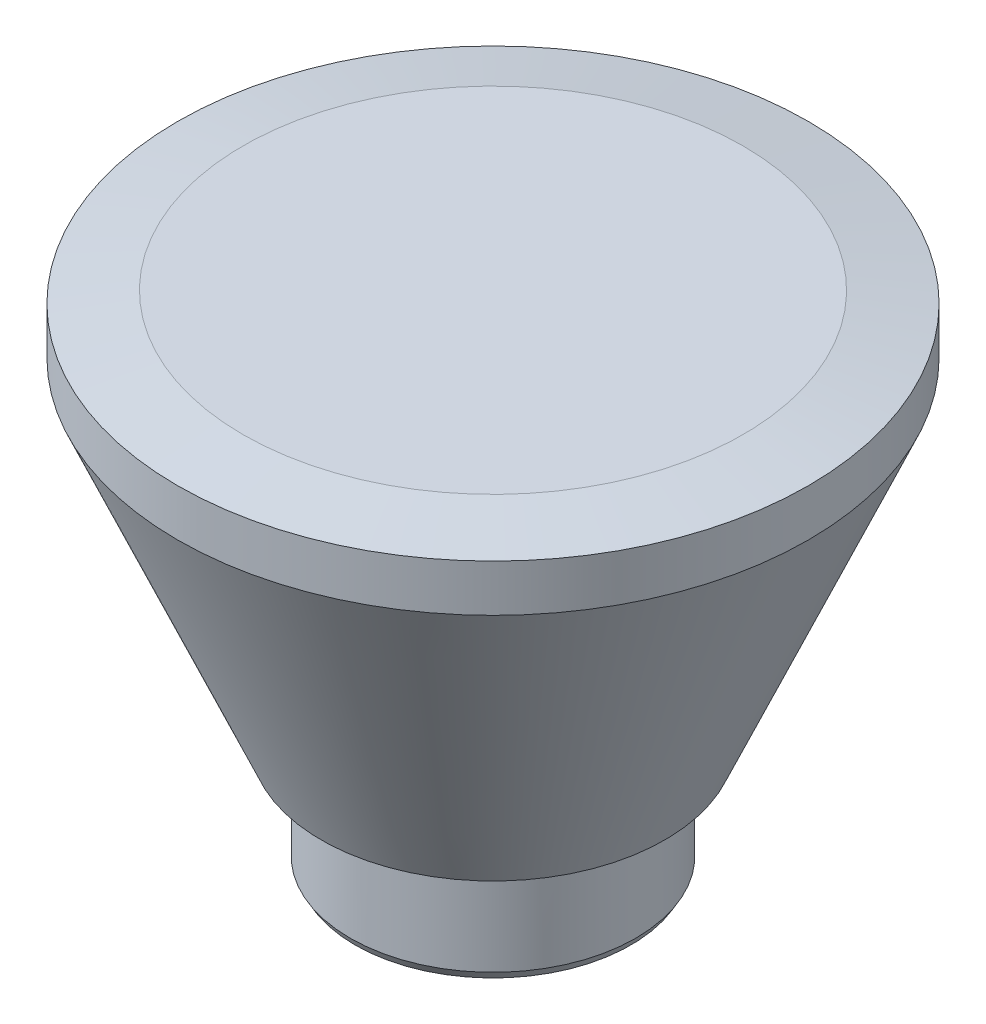
SolidWorks part; units mm, degrees
material "PLA"
ref_plane "Front Plane" through (0, 0, 0) normal (0, 0, 1) x (1, 0, 0)
ref_plane "Top Plane" through (0, 0, 0) normal (0, 1, 0) x (1, 0, 0)
ref_plane "Right Plane" through (0, 0, 0) normal (1, 0, 0) x (0, 0, -1)
sketch "Sketch1" plane through (0, 0, 0) normal (0, 0, 1) x (1, 0, 0)
  line L0 (-19, 22.4817) -> (-15.0608, 23.1763)
  line L2 (0, -1.5737) -> (0, 23.1763)
  line L3 (0, 23.1763) -> (-15.0608, 23.1763)
  line L4 (-19, 19.6513) -> (-19, 22.4817)
  line L6 (-5.6, 3.4263) -> (-3, 3.4263)
  line L12 (-8.6, -0.3237) -> (-8.6, -6.8237)
  line L13 (-8.6, -6.8237) -> (-5.6, -6.8237)
  line L14 (-5.6, -6.8237) -> (-5.6, 3.4263)
  line L15 (-10.35, 0.6763) -> (-10.35, -0.3237) construction
  line L16 (-10.35, -0.3237) -> (-8.6, -0.3237)
  line L20 (-3, 3.4263) -> (-3, -1.5737)
  line L21 (-3, -1.5737) -> (0, -1.5737)
  line L22 (-11.35, 0.6763) -> (-11.35, 1.6763) construction
  line L23 (-11.35, 1.6763) -> (-12.35, 1.6763) construction
  line L24 (-12.35, 1.6763) -> (-12.35, 2.6763) construction
  line L25 (-12.35, 2.6763) -> (-13.35, 2.6763) construction
  line L26 (-13.35, 2.6763) -> (-13.35, 3.6763) construction
  line L27 (-13.35, 3.6763) -> (-14.35, 3.6763) construction
  line L28 (-14.35, 3.6763) -> (-14.35, 4.6763) construction
  line L29 (-14.35, 4.6763) -> (-15.35, 4.6763) construction
  line L30 (-15.35, 4.6763) -> (-15.35, 5.6763) construction
  line L31 (-15.35, 5.6763) -> (-16.35, 5.6763) construction
  line L32 (-19, 19.6513) -> (-10.35, -0.3237)
  line L37 (-16.35, 5.6763) -> (-16.35, 3.6763) construction
  line L38 (-16.35, 3.6763) -> (-14.35, 3.6763) construction
  line L39 (-14.35, 3.6763) -> (-14.35, 1.6763) construction
  line L40 (-14.35, 1.6763) -> (-12.35, 1.6763) construction
  line L41 (-12.35, 1.6763) -> (-12.35, 0.6763)
  line L44 (-10.35, 0.6763) -> (-10.35, 0.8513) construction
  line L45 (-10.35, 0.8513) -> (-10.85, 0.8513) construction
  line L46 (-10.85, 0.8513) -> (-10.85, 2.0263) construction
  line L47 (-11.35, 2.0263) -> (-11.35, 3.2013) construction
  line L48 (-11.35, 3.2013) -> (-11.85, 3.2013) construction
  line L49 (-11.85, 3.2013) -> (-11.85, 4.3763) construction
  line L50 (-11.85, 4.3763) -> (-12.35, 4.3763) construction
  line L51 (-12.35, 4.3763) -> (-12.35, 5.5513) construction
  line L52 (-12.35, 5.5513) -> (-12.85, 5.5513) construction
  line L53 (-12.85, 5.5513) -> (-12.85, 6.7263) construction
  line L54 (-12.85, 6.7263) -> (-13.35, 6.7263) construction
  line L55 (-13.35, 6.7263) -> (-13.35, 7.9013) construction
  line L56 (-13.35, 7.9013) -> (-13.85, 7.9013) construction
  line L57 (-13.85, 7.9013) -> (-13.85, 9.0763) construction
  line L58 (-13.85, 9.0763) -> (-14.35, 9.0763) construction
  line L59 (-14.35, 9.0763) -> (-14.35, 10.2513) construction
  line L60 (-14.35, 10.2513) -> (-14.85, 10.2513) construction
  line L61 (-14.85, 10.2513) -> (-14.85, 11.4263) construction
  line L62 (-14.85, 11.4263) -> (-15.35, 11.4263) construction
  line L63 (-15.35, 11.4263) -> (-15.35, 12.6013) construction
  line L64 (-10.85, 2.0263) -> (-11.35, 2.0263) construction
  line L65 (-15.35, 12.6013) -> (-15.85, 12.6013) construction
  line L66 (-15.85, 12.6013) -> (-15.85, 13.7763) construction
  line L67 (-15.85, 13.7763) -> (-16.35, 13.7763) construction
  line L68 (-16.35, 13.7763) -> (-16.35, 14.9513) construction
  line L69 (-16.35, 14.9513) -> (-16.85, 14.9513) construction
  line L70 (-16.85, 14.9513) -> (-16.85, 16.1263) construction
  line L71 (-16.85, 16.1263) -> (-17.35, 16.1263) construction
  line L72 (-17.35, 16.1263) -> (-17.35, 17.3013) construction
  line L73 (-17.35, 17.3013) -> (-17.85, 17.3013) construction
  line L74 (-17.85, 17.3013) -> (-17.85, 18.4763) construction
  line L75 (-17.85, 18.4763) -> (-18.35, 18.4763) construction
  line L76 (-18.35, 18.4763) -> (-18.35, 19.6513) construction
  line L77 (-18.35, 19.6513) -> (-19, 19.6513) construction
  dimension "D6" = 4
  dimension "D7" = 10
  dimension "D1" = 5.6
  dimension "D4" = 19
  dimension "D10" = 1.75
  dimension "D2" = 10.25
  dimension "D8" = 6.5
  dimension "D11" = 3
  dimension "D12" = 5
  dimension "Bearing ID" = 8.6
  dimension "D3" = 30
  dimension "D9" = 0.175
  dimension "D13" = 0.5
  dimension "D14" = 1.175
revolve "Revolve1" add sketch "Sketch1" angle 360 about L2
sketch "Sketch3" plane through (0, -1.5737, 0) normal (0, -1, 0) x (1, 0, 0)
  line L0 (0.75, 1.85) -> (0, 1.1)
  line L1 (6.25, -1.85) -> (0.75, -1.85)
  line L2 (7, -1.1) -> (7, 1.1)
  line L3 (6.25, 1.85) -> (0.75, 1.85)
  line L4 (0, -1.1) -> (0, 1.1)
  line L5 (7, -1.85) -> (0, 1.85) construction
  line L6 (7, 1.85) -> (0, -1.85) construction
  line L7 (0.75, -1.85) -> (0, -1.1)
  line L8 (7, -1.1) -> (6.25, -1.85)
  line L9 (7, 1.1) -> (6.25, 1.85)
  point P0 (3.5, 0)
  point P14 (-2, 0)
  point P15 (0, 0)
extrude "Cut-Extrude1" cut sketch "Sketch3" against normal up to surface and the other way up to surface up to face at (0, 3.4263, -3) other way up to face at (0, -6.8237, -5.6)
chamfer "Chamfer1" distance 1 angle 45 1 edges at (-5.6, -6.8237, 0)
chamfer "Chamfer2" distance 0.5 angle 30 1 edges at (0, -6.8237, -8.6)
equation "\"BearingID\"=8.6"
equation "\"Bearing ID@Sketch1\"=\"BearingID\""
